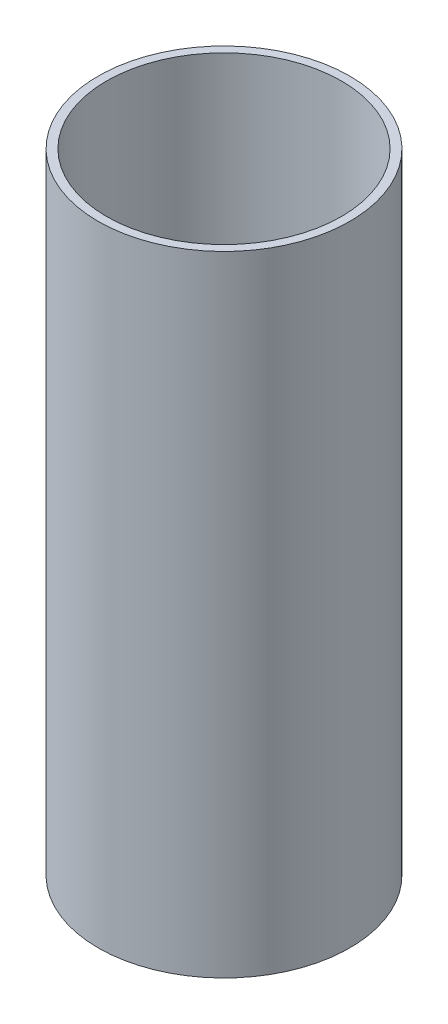
SolidWorks part; units mm, degrees
ref_plane "Front Plane" through (0, 0, 0) normal (0, 0, 1) x (1, 0, 0)
ref_plane "Top Plane" through (0, 0, 0) normal (0, 1, 0) x (1, 0, 0)
ref_plane "Right Plane" through (0, 0, 0) normal (1, 0, 0) x (0, 0, -1)
sketch "Sketch1" plane through (0, 0, 0) normal (0, 1, 0) x (1, 0, 0)
  circle A0 centre (0, 0) radius 28
  circle A1 centre (0, 0) radius 30
  dimension "D1" = 60
  dimension "D2" = 2
extrude "Boss-Extrude1" add sketch "Sketch1" along normal blind 150
